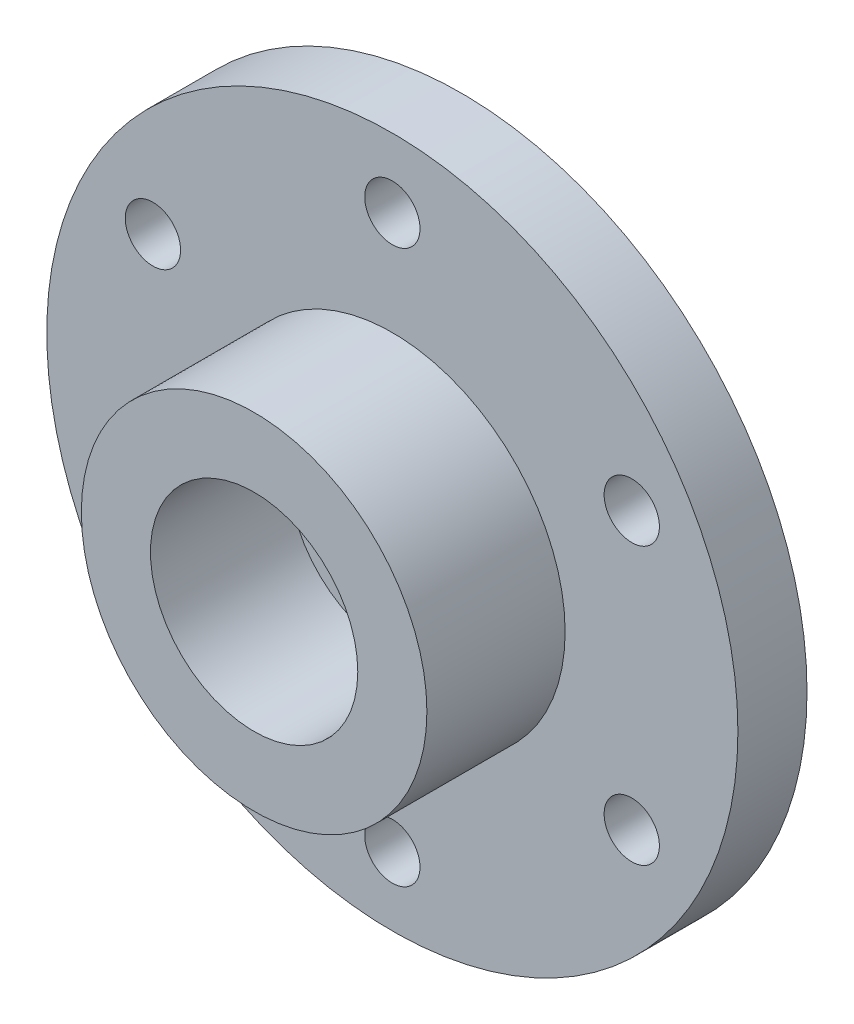
SolidWorks part; units mm, degrees
material "Plain Carbon Steel"
ref_plane "Front Plane" through (0, 0, 0) normal (0, 0, 1) x (1, 0, 0)
ref_plane "Top Plane" through (0, 0, 0) normal (0, 1, 0) x (1, 0, 0)
ref_plane "Right Plane" through (0, 0, 0) normal (1, 0, 0) x (0, 0, -1)
sketch "Sketch1" plane through (0, 0, 0) normal (0, 0, 1) x (1, 0, 0)
  circle A0 centre (0, 0) radius 25
  circle A1 centre (0, 0) radius 20 construction
  circle A2 centre (0, 20) radius 2
  circle A3 centre (17.3205, 10) radius 2
  circle A4 centre (17.3205, -10) radius 2
  circle A5 centre (0, -20) radius 2
  circle A6 centre (-17.3205, -10) radius 2
  circle A7 centre (-17.3205, 10) radius 2
  point P19 (0, 0)
  dimension "D1" = 50
  dimension "D2" = 40
  dimension "D3" = 4
  dimension "D4" = 6
extrude "Boss-Extrude1" add sketch "Sketch1" along normal blind 5
sketch "Sketch2" plane through (0, 0, 5) normal (0, 0, 1) x (1, 0, 0)
  circle A0 centre (0, 0) radius 7.5
  circle A1 centre (0, 0) radius 12.5
  dimension "D1" = 15
  dimension "D2" = 25
extrude "Boss-Extrude2" add sketch "Sketch2" along normal blind 10
